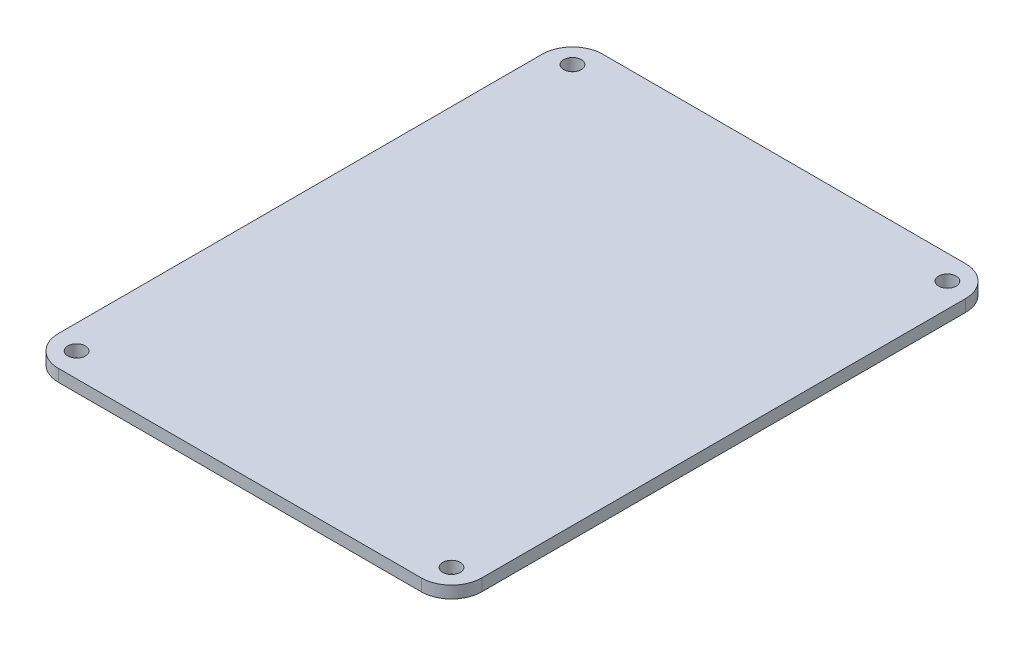
SolidWorks part; units mm, degrees
ref_plane "Front Plane" through (0, 0, 0) normal (0, 0, 1) x (1, 0, 0)
ref_plane "Top Plane" through (0, 0, 0) normal (0, 1, 0) x (1, 0, 0)
ref_plane "Right Plane" through (0, 0, 0) normal (1, 0, 0) x (0, 0, -1)
sketch "Sketch1" plane through (0, 0, 0) normal (0, 1, 0) x (1, 0, 0)
  line L1 (-44.45, -57.15) -> (44.45, -57.15)
  line L2 (-44.45, -57.15) -> (-44.45, 57.15)
  line L3 (-44.45, 57.15) -> (44.45, 57.15)
  line L4 (44.45, -57.15) -> (44.45, 57.15)
  line L5 (-44.45, -57.15) -> (44.45, 57.15) construction
  line L6 (-44.45, 57.15) -> (44.45, -57.15) construction
  point P0 (0, 0)
  dimension "D1" = 114.3
  dimension "D2" = 88.9
extrude "Boss-Extrude1" add sketch "Sketch1" along normal blind 2.54
sketch "Sketch2" plane through (0, 2.54, 0) normal (0, 1, 0) x (1, 0, 0)
  line L0 (-44.45, 57.15) -> (-44.45, -57.15) construction
  line L1 (-39.37, -52.07) -> (39.37, -52.07) construction
  line L2 (-39.37, -52.07) -> (-39.37, 52.07) construction
  line L3 (-39.37, 52.07) -> (39.37, 52.07) construction
  line L4 (39.37, -52.07) -> (39.37, 52.07) construction
  line L5 (-39.37, -52.07) -> (39.37, 52.07) construction
  line L6 (-39.37, 52.07) -> (39.37, -52.07) construction
  line L7 (44.45, 57.15) -> (-44.45, 57.15) construction
  circle A0 centre (-39.37, 52.07) radius 1.8415
  circle A1 centre (39.37, 52.07) radius 1.8415
  circle A2 centre (-39.37, -52.07) radius 1.8415
  circle A3 centre (39.37, -52.07) radius 1.8415
  point P0 (0, 0)
  dimension "D1" = 3.683
  dimension "D2" = 5.08
  dimension "D3" = 5.08
extrude "Cut-Extrude1" cut sketch "Sketch2" against normal through all
fillet "Fillet1" radius 6.35 4 edges at (-44.45, 1.27, 57.15) (44.45, 1.27, 57.15) (44.45, 1.27, -57.15) (-44.45, 1.27, -57.15)
